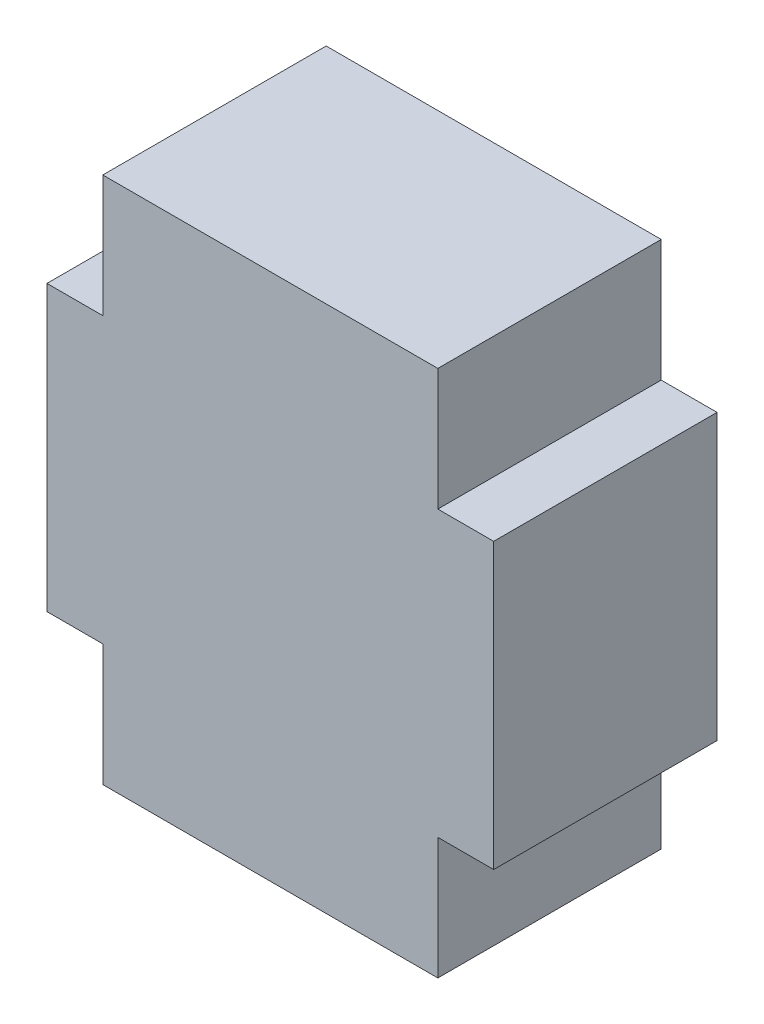
SolidWorks part; units mm, degrees
ref_plane "前视基准面" through (0, 0, 0) normal (0, 0, 1) x (1, 0, 0)
ref_plane "上视基准面" through (0, 0, 0) normal (0, 1, 0) x (1, 0, 0)
ref_plane "右视基准面" through (0, 0, 0) normal (1, 0, 0) x (0, 0, -1)
sketch "草图1" plane through (0, 0, 0) normal (0, 0, 1) x (1, 0, 0)
  line L0 (-0.825, -1.3) -> (-0.825, -0.7)
  line L1 (-0.825, -0.7) -> (-1.1, -0.7)
  line L2 (-1.1, -0.7) -> (-1.1, 0.7)
  line L3 (-1.1, 0.7) -> (-0.825, 0.7)
  line L4 (-0.825, 0.7) -> (-0.825, 1.3)
  line L5 (-0.825, 1.3) -> (0.825, 1.3)
  line L6 (0.825, 1.3) -> (0.825, 0.7)
  line L7 (0.825, 0.7) -> (1.1, 0.7)
  line L8 (1.1, 0.7) -> (1.1, -0.7)
  line L9 (1.1, -0.7) -> (0.825, -0.7)
  line L10 (0.825, -0.7) -> (0.825, -1.3)
  line L11 (0.825, -1.3) -> (-0.825, -1.3)
extrude "Component_Outline" add sketch "草图1" along normal blind 1.1 separate body
sketch3d "3D草图1"
  line L0 (0, 0, 0) -> (1, 0, 0)
  line L1 (0, 0, 0) -> (0, 1, 0)
  line L2 (0, 0, 0) -> (0, 0, 1)
  point P0 (0, 0, 0)
